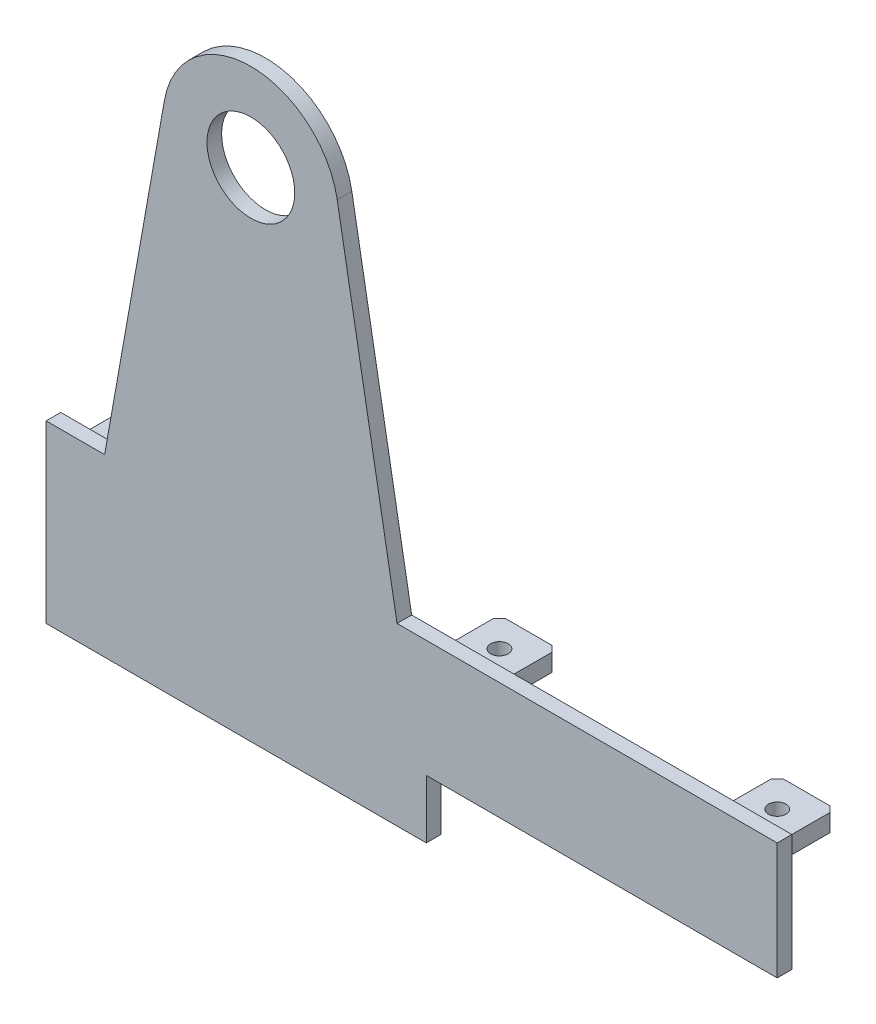
SolidWorks part; units mm, degrees
material "Сталь 3 ГОСТ 535-88"
ref_plane "Спереди" through (0, 0, 0) normal (0, 0, 1) x (1, 0, 0)
ref_plane "Сверху" through (0, 0, 0) normal (0, 1, 0) x (1, 0, 0)
ref_plane "Справа" through (0, 0, 0) normal (1, 0, 0) x (0, 0, -1)
sketch "Эскиз1" plane through (0, 0, 0) normal (0, 0, 1) x (1, 0, 0)
  line L0 (-65, 0) -> (-65, 60)
  line L1 (-65, 60) -> (185, 60)
  line L2 (185, 60) -> (185, 20)
  line L3 (185, 20) -> (65, 20)
  line L4 (65, 20) -> (65, 0)
  line L6 (65, 0) -> (-65, 0)
  dimension "D1" = 130
  dimension "D2" = 60
  dimension "D3" = 40
  dimension "D4" = 250
extrude "Бобышка-Вытянуть1" add sketch "Эскиз1" against normal blind 5
sketch "Эскиз2" plane through (0, 0, 0) normal (0, 0, 1) x (1, 0, 0)
  line L0 (-45, 60) -> (-24.538, 175.2446)
  line L1 (185, 60) -> (-65, 60) construction
  line L2 (34.538, 175.2446) -> (55, 60)
  line L3 (-45, 60) -> (55, 60)
  line L4 (5, 204.1229) -> (5, 138.6821) construction
  arc A0 (-24.538, 175.2446) -> (34.538, 175.2446) centre (5, 170) cw
  circle A1 centre (5, 170) radius 15
  point P12 (5, 60)
  dimension "D2" = 30
  dimension "D4" = 30
  dimension "D1" = 20
  dimension "D3" = 140
  dimension "D5" = 100
extrude "Бобышка-Вытянуть2" add sketch "Эскиз2" against normal up to surface (5 mm away) up to face at (61.6667, 26.6667, -5)
ref_plane "Плоскость1" through (0, 55, 0) normal (0, 1, 0) x (1, 0, 0)
sketch "Эскиз3" plane through (0, 55, 0) normal (0, 1, 0) x (1, 0, 0)
  line L7 (185, 5) -> (185, 0) construction
  line L8 (185, 5) -> (55, 5) construction
  line L9 (180, 5) -> (160, 5)
  line L10 (180, 5) -> (180, 25)
  line L11 (180, 25) -> (160, 25)
  line L12 (160, 5) -> (160, 25)
  line L13 (170, 25) -> (170, 5) construction
  line L14 (180, 15) -> (160, 15) construction
  circle A1 centre (170, 15) radius 3
  dimension "D2" = 6
  dimension "D1" = 20
  dimension "D3" = 15
extrude "Бобышка-Вытянуть3" add sketch "Эскиз3" against normal blind 6 separate body
ref_plane "Плоскость2" through (60, 0, 0) normal (1, 0, 0) x (0, 0, -1)
chamfer "Фаска1" distance 2 angle 45 4 edges at (160, 52, -5) (160, 52, -25) (180, 52, -25) (180, 52, -5)
mirror "Зеркальное отражение1" about plane through (60, 0, 0) normal (1, 0, 0) of bodies 105
sketch "Эскиз4" plane through (0, 55, 0) normal (0, 1, 0) x (1, 0, 0)
  line L0 (185, 5) -> (55, 5) construction
  line L1 (65, 5) -> (85, 5)
  line L2 (65, 5) -> (65, 25)
  line L3 (65, 25) -> (85, 25)
  line L4 (85, 5) -> (85, 25)
  line L5 (75, 25) -> (75, 5) construction
  line L6 (65, 15) -> (85, 15) construction
  line L8 (160, 23) -> (160, 7) construction
  circle A0 centre (75, 15) radius 3
  point P0 (75, 15)
  dimension "D3" = 6
  dimension "D1" = 20
  dimension "D2" = 75
extrude "Бобышка-Вытянуть4" add sketch "Эскиз4" against normal blind 6 separate body
chamfer "Фаска2" distance 2 angle 45 4 edges at (85, 52, -5) (65, 52, -5) (85, 52, -25) (65, 52, -25)
